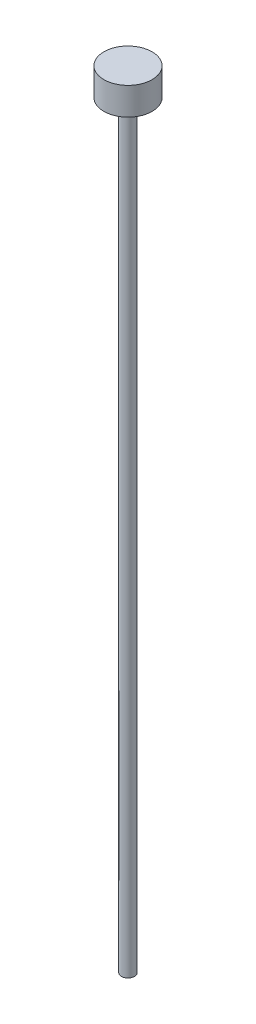
SolidWorks part; units mm, degrees
ref_plane "Plano frontal" through (0, 0, 0) normal (0, 0, 1) x (1, 0, 0)
ref_plane "Plano superior" through (0, 0, 0) normal (0, 1, 0) x (1, 0, 0)
ref_plane "Plano direito" through (0, 0, 0) normal (1, 0, 0) x (0, 0, -1)
sketch "Esboço1" plane through (0, 0, 0) normal (0, 1, 0) x (1, 0, 0)
  circle A0 centre (0, 0) radius 0.95
extrude "Ressalto-extrusão1" add sketch "Esboço1" along normal blind 110
sketch "Esboço2" plane through (0, 110, 0) normal (0, 1, 0) x (1, 0, 0)
  circle A0 centre (0, 0) radius 3.5
extrude "Ressalto-extrusão2" add sketch "Esboço2" along normal blind 4
fillet "Filete3" radius 1 1 edges at (0, 110, 0.95)
